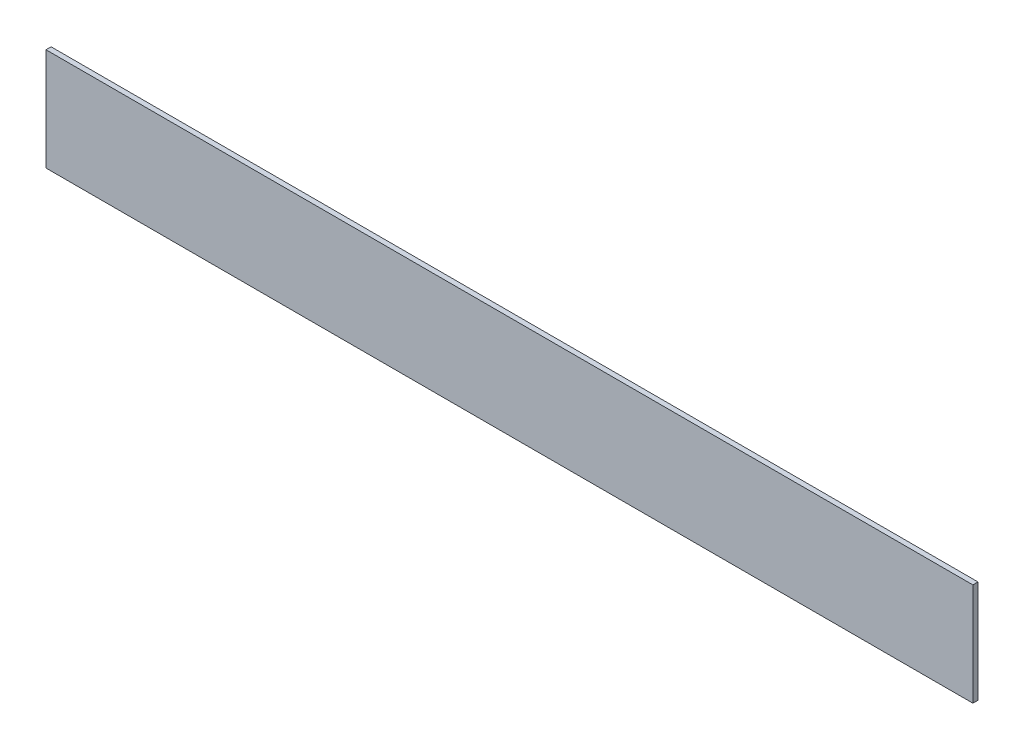
SolidWorks part; units mm, degrees
ref_plane "Plano frontal" through (0, 0, 0) normal (0, 0, 1) x (1, 0, 0)
ref_plane "Plano superior" through (0, 0, 0) normal (0, 1, 0) x (1, 0, 0)
ref_plane "Plano direito" through (0, 0, 0) normal (1, 0, 0) x (0, 0, -1)
sketch "Sketch1" plane through (0, 0, 0) normal (0, 0, 1) x (1, 0, 0)
  line L1 (904.5, 100) -> (-904.5, 100)
  line L2 (904.5, 100) -> (904.5, -100)
  line L3 (904.5, -100) -> (-904.5, -100)
  line L4 (-904.5, 100) -> (-904.5, -100)
  line L5 (904.5, 100) -> (-904.5, -100) construction
  line L6 (904.5, -100) -> (-904.5, 100) construction
  point P0 (0, 0)
extrude "Boss-Extrude1" add sketch "Sketch1" along normal blind 10
